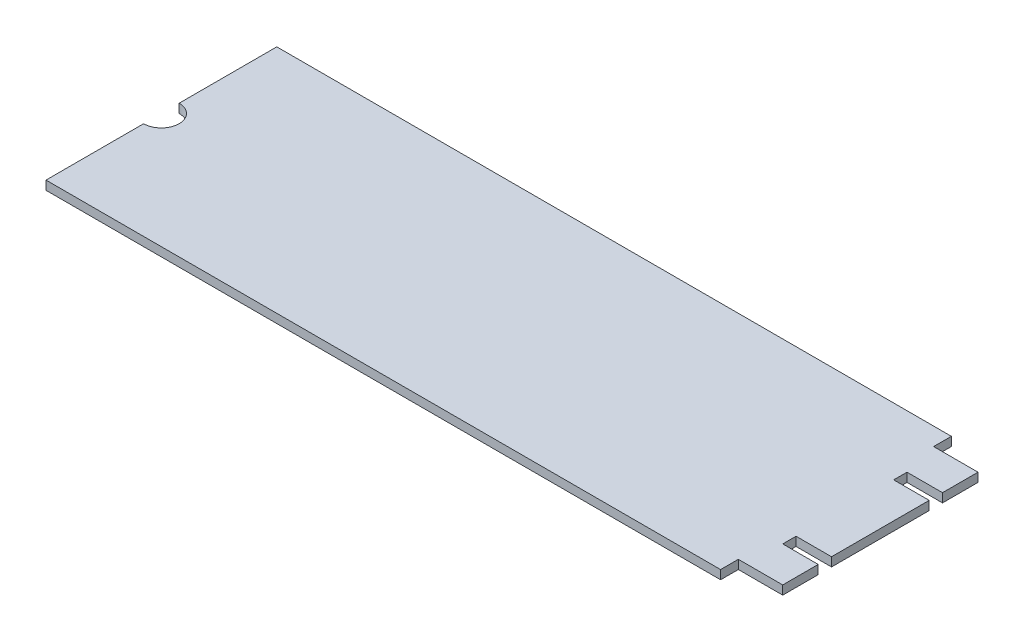
SolidWorks part; units mm, degrees
ref_plane "前基準面" through (0, 0, 0) normal (0, 0, 1) x (1, 0, 0)
ref_plane "上基準面" through (0, 0, 0) normal (0, 1, 0) x (1, 0, 0)
ref_plane "右基準面" through (0, 0, 0) normal (1, 0, 0) x (0, 0, -1)
sketch "草圖1" plane through (0, 0, 0) normal (0, 1, 0) x (1, 0, 0)
  line L0 (0, 0) -> (76, 0)
  line L1 (76, 0) -> (76, 2)
  line L2 (76, 2) -> (81, 2)
  line L3 (81, 2) -> (81, 6)
  line L4 (81, 6) -> (77, 6)
  line L5 (77, 6) -> (77, 7.5)
  line L6 (77, 7.5) -> (81, 7.5)
  line L7 (81, 7.5) -> (81, 18.5)
  line L8 (81, 18.5) -> (77, 18.5)
  line L9 (77, 18.5) -> (77, 20)
  line L10 (77, 20) -> (81, 20)
  line L11 (81, 20) -> (81, 24)
  line L12 (81, 24) -> (76, 24)
  line L13 (76, 24) -> (76, 26)
  line L14 (76, 26) -> (0, 26)
  line L15 (0, 26) -> (0, 15)
  line L16 (0, 11) -> (0, 0)
  arc A0 (0, 15) -> (0, 11) centre (0, 13) cw
  point P20 (0, 10.0056)
  dimension "D1" = 76
  dimension "D2" = 2
  dimension "D3" = 5
  dimension "D4" = 4
  dimension "D5" = 4
  dimension "D6" = 1.5
  dimension "D7" = 11
  dimension "D8" = 4
  dimension "D9" = 2
extrude "填料-伸長1" add sketch "草圖1" along normal blind 1
